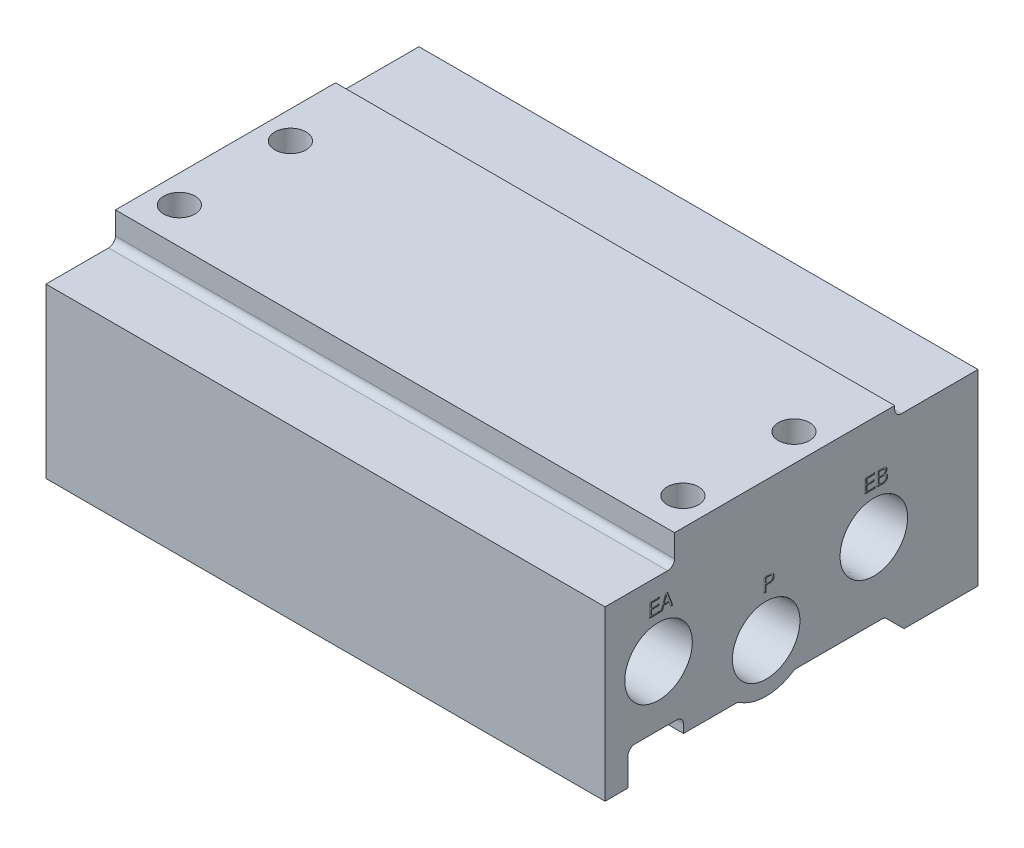
SolidWorks part; units mm, degrees
material "6061-T6 (SS)"
ref_plane "Front" through (0, 0, 0) normal (0, 0, 1) x (1, 0, 0)
ref_plane "Top" through (0, 0, 0) normal (0, 1, 0) x (1, 0, 0)
ref_plane "Right" through (0, 0, 0) normal (1, 0, 0) x (0, 0, -1)
sketch "Alum Ext Sketch" plane through (0, 0, 0) normal (1, 0, 0) x (0, 0, -1)
  line L1 (-26.85, 0) -> (26.85, 0)
  line L2 (-26.85, 0) -> (-26.85, -28.5)
  line L4 (26.85, 0) -> (26.85, -28.5)
  line L7 (0, 5.7104) -> (0, -31.2342) construction
  line L8 (-26.85, -28.5) -> (26.85, -28.5)
  dimension "Depth" = 53.7
  dimension "Height" = 28.5
extrude "Alum Ext" add sketch "Alum Ext Sketch" against normal up to surface (80.5 mm away)
sketch "Bottom_Profile 20 Sketch" [suppressed] plane through (0, 0, 0) normal (1, 0, 0) x (0, 0, -1)
  line L0 (-1, 0) -> (-1, -38.4475) construction
  line L1 (-21.54, -20) -> (-21.54, -13.45)
  line L2 (-24.5, -20) -> (24.5, -20) construction
  line L3 (-21.54, -13.45) -> (-21.1875, -13.45)
  line L4 (-13.8125, -13.45) -> (-4.6875, -13.45)
  line L5 (11.8125, -13.45) -> (2.6875, -13.45)
  line L6 (21.54, -13.45) -> (19.1875, -13.45)
  line L7 (21.54, -20) -> (21.54, -13.45)
  line L8 (24.5, -20) -> (24.5, 0) construction
  line L9 (-24.5, 0) -> (-24.5, -20) construction
  line L10 (24.5, 0) -> (-24.5, 0) construction
  line L11 (21.54, -16.725) -> (24.5, -16.725) construction
  line L12 (-21.54, -16.725) -> (-24.5, -16.725) construction
  line L13 (-24.5, -20) -> (-24.5, 0) construction
  line L14 (-21.54, -20) -> (21.54, -20)
  line L15 (-10.2716, -5) -> (-8.2284, -5)
  line L17 (-10.9481, -11.65) -> (-7.5519, -11.65)
  line L18 (-1, 9.9528) -> (-1, -11.3216) construction
  line L19 (8.9481, -11.65) -> (5.5519, -11.65)
  line L20 (8.2716, -5) -> (6.2284, -5)
  line L21 (24.5, 0) -> (-24.5, 0) construction
  arc A0 (-21.1875, -13.45) -> (-13.8125, -13.45) centre (-17.5, -7.5) ccw
  arc A1 (-4.6875, -13.45) -> (2.6875, -13.45) centre (-1, -7.5) ccw
  arc A2 (19.1875, -13.45) -> (11.8125, -13.45) centre (15.5, -7.5) cw
  arc A3 (-10.7535, -5.6333) -> (-11.3849, -10.9067) centre (-17.5, -7.5) cw
  arc A4 (-10.7535, -5.6333) -> (-10.2716, -5) centre (-10.2716, -5.5) cw
  arc A5 (-10.9481, -11.65) -> (-11.3849, -10.9067) centre (-10.9481, -11.15) cw
  arc A6 (-7.5519, -11.65) -> (-7.1151, -10.9067) centre (-7.5519, -11.15) ccw
  arc A7 (-7.7465, -5.6333) -> (-8.2284, -5) centre (-8.2284, -5.5) ccw
  arc A8 (-7.7465, -5.6333) -> (-7.1151, -10.9067) centre (-1, -7.5) ccw
  arc A9 (5.7465, -5.6333) -> (5.1151, -10.9067) centre (-1, -7.5) cw
  arc A10 (5.7465, -5.6333) -> (6.2284, -5) centre (6.2284, -5.5) cw
  arc A11 (5.5519, -11.65) -> (5.1151, -10.9067) centre (5.5519, -11.15) cw
  arc A12 (8.9481, -11.65) -> (9.3849, -10.9067) centre (8.9481, -11.15) ccw
  arc A13 (8.7535, -5.6333) -> (8.2716, -5) centre (8.2716, -5.5) ccw
  arc A14 (8.7535, -5.6333) -> (9.3849, -10.9067) centre (15.5, -7.5) ccw
  dimension "D1" = 23.5
  dimension "Wall_Radius" = 7
  dimension "D2" = 0.5
  dimension "D4" = 5
  dimension "D3" = 1.8
  dimension "Thickness" = 2.96
  dimension "Port_Loc_Z" = 16.5
  dimension "Port_Loc_Y" = 12.5
  dimension "Body_Thickness" = 13.45
extrude "Bottom_Profile 20" [suppressed] cut sketch "Bottom_Profile 20 Sketch" against normal through all
fillet "Ext_Fillets" [suppressed] radius 0.25
sketch "MGT_Holes Sketch" plane through (0, 0, 0) normal (0, 1, 0) x (1, 0, 0)
  line L1 (-40.25, 26.85) -> (-40.25, -50.1534) construction
  line L2 (-80.5, 26.85) -> (0, 26.85) construction
  line L3 (0, 0) -> (0, 12.4211) construction
  line L4 (-80.5, -26.85) -> (0, -26.85) construction
  line L6 (-80.5, -26.85) -> (-80.5, 26.85) construction
  circle A0 centre (-76.5, 4.35) radius 2.25
  circle A1 centre (-76.5, -11.65) radius 2.25
  circle A4 centre (-4, 4.35) radius 2.25
  circle A5 centre (-4, -11.65) radius 2.25
  dimension "Dia" = 4.5
  dimension "Loc_X" = 4
  dimension "Loc_Z" = 15.2
  dimension "C_2_C" = 16
extrude "MGT_Holes" cut sketch "MGT_Holes Sketch" against normal through all
sketch "Top_Profile_41 Sketch" plane through (0, 0, 0) normal (1, 0, 0) x (0, 0, -1)
  line L0 (-26.85, -4.25) -> (-16.85, -4.25)
  line L1 (-16.85, -4.25) -> (-16.85, 0)
  line L2 (26.85, 0) -> (-26.85, 0) construction
  line L3 (14.85, 0) -> (14.85, -1.5)
  line L4 (14.85, -1.5) -> (26.85, -1.5)
  line L5 (26.85, -28.5) -> (26.85, 0) construction
  line L6 (-26.85, -28.5) -> (26.85, -28.5) construction
  line L7 (-26.85, 0) -> (-26.85, -28.5) construction
  line L8 (26.85, -1.5) -> (26.85, 0)
  line L9 (-26.85, 0) -> (-26.85, -4.25)
  line L10 (26.85, 0) -> (14.85, 0)
  line L11 (-16.85, 0) -> (-26.85, 0)
  dimension "Back" = 12
  dimension "Back Height" = 27
  dimension "Front" = 10
  dimension "Front_Height" = 24.25
extrude "Top_Profile_41" cut sketch "Top_Profile_41 Sketch" against normal through all
sketch "Bottom_Profile_41 Sketch" plane through (0, 0, 0) normal (1, 0, 0) x (0, 0, -1)
  line L0 (16.2, -28.5) -> (13.4, -25.7)
  line L1 (-26.85, -28.5) -> (26.85, -28.5) construction
  line L2 (13.4, -25.7) -> (0.4132, -25.7)
  line L3 (-15.55, -25.7) -> (-15.55, -23.5)
  line L4 (-15.55, -23.5) -> (-23.55, -23.5)
  line L5 (-23.55, -23.5) -> (-23.55, -28.5)
  line L6 (26.85, -28.5) -> (-26.85, -28.5) construction
  line L7 (26.85, -28.5) -> (26.85, -1.5) construction
  line L8 (-26.85, -4.25) -> (-26.85, -28.5) construction
  line L9 (-26.85, -28.5) -> (-26.85, -4.25) construction
  line L10 (-7.7132, -25.7) -> (-15.55, -25.7)
  line L11 (-23.55, -28.5) -> (16.2, -28.5)
  arc A0 (-7.7132, -25.7) -> (0.4132, -25.7) centre (-3.65, -20) ccw
  dimension "D1" = 8.5
  dimension "D2" = 23.2
  dimension "Radius" = 7
  dimension "Back_Width" = 13.45
  dimension "Back_Depth" = 2.8
  dimension "Front_Width" = 3.3
  dimension "Front_Depth" = 5
  dimension "Groove" = 8
  dimension "Angle" = 45
extrude "Bottom_Profile_41" cut sketch "Bottom_Profile_41 Sketch" against normal through all
fillet "Rounds_41" radius 1 7 edges at (-40.25, -4.25, 16.85) (-40.25, -1.5, -14.85) (-40.25, -25.7, -0.4132) (-40.25, -23.5, 23.55) (-40.25, -23.5, 15.55) (-40.25, -25.7, 7.7132) (-40.25, -25.7, -13.4)
sketch "Profile_42 Sketch" [suppressed] plane through (0, 0, 0) normal (1, 0, 0) x (0, 0, -1)
  line L0 (-13.9, -32) -> (-12.9, -31)
  line L1 (-27.85, -32) -> (27.85, -32) construction
  line L2 (-12.9, -31) -> (12.9, -31)
  line L3 (12.9, -31) -> (13.9, -32)
  line L4 (13.9, -32) -> (-13.9, -32)
  line L5 (0, 0) -> (0, -41.5568) construction
  dimension "Width" = 25.8
  dimension "Angle" = 90
  dimension "Depth" = 1
extrude "Profile_42" [suppressed] cut sketch "Profile_42 Sketch" against normal through all
fillet "Fillets_42" [suppressed] radius 0.5
sketch "20 Port Designations Sketch" [suppressed] plane through (2.9671, 0, 3.015) normal (0, 1, 0) x (0, 0, 1)
  line L0 (21.485, -51.4671) -> (-27.515, -51.4671) construction
  line L2 (-27.515, -51.4671) -> (-27.515, -2.9671) construction
  line L3 (21.485, -51.4671) -> (21.485, -2.9671) construction
  text T0 "EA"
  text T1 "P" font "Swis721 BT" height 3.5
  text T2 "EB" font "Swis721 BT" height 3.5
  dimension "D1" = 3
  dimension "D2" = 4
  dimension "D3" = 23
  dimension "D4" = 11
extrude "20 Port Designations" [suppressed] cut sketch "20 Port Designations Sketch" against normal blind 0.1
sketch "20 Port Designations2 Sketch" [suppressed] plane through (-31.3648, 0, 0.1552) normal (0, 1, 0) x (0, 0, -1)
  line L0 (24.6552, -31.3648) -> (-24.3448, -31.3648) construction
  line L1 (24.6552, 17.1352) -> (24.6552, -31.3648) construction
  line L2 (-24.3448, 17.1352) -> (-24.3448, -31.3648) construction
  text T0 "EB"
  text T1 "P"
  text T2 "EA"
  dimension "D1" = 3
  dimension "D2" = 26.5
  dimension "D3" = 4
  dimension "D4" = 11
extrude "20 Port Designations2" [suppressed] cut sketch "20 Port Designations2 Sketch" against normal blind 0.1
hole_wizard "Ports" positions "Ports Loc Sketch" profile "Ports Profile Sketch" size "1/8" standard "ISO"
sketch "Ports Loc Sketch" plane through (0, 0, 0) normal (1, 0, 0) x (0, 0, -1)
  line L1 (-3.65, -20) -> (-3.65, -0.9405) construction
  line L5 (-26.85, -28.5) -> (-23.55, -28.5) construction
  line L7 (-26.85, -4.25) -> (-26.85, -28.5) construction
  point P0 (-3.65, -20)
  point P1 (11.85, -14.9)
  point P3 (-19.15, -14.9)
  dimension "Loc_Z" = 23.2
  dimension "C_2_C-Z" = 15.5
  dimension "C_2_C-Y" = 8.5
  dimension "Loc_Y" = 13.6
sketch "Ports Profile Sketch" plane through (0, -20, 3.65) normal (0, 1, 0) x (0, 0, -1)
  line L0 (0, 0) -> (0, 22.45)
  line L1 (3.95, 18.5) -> (0, 22.45)
  line L2 (-3.95, 18.5) -> (0, 22.45) construction
  line L3 (3.95, 18.5) -> (3.95, 7.4)
  line L4 (3.95, 7.4) -> (4.633, 7.4)
  line L5 (4.633, 7.4) -> (4.864, 0)
  line L6 (-4.633, 7.4) -> (-4.864, 0) construction
  line L7 (4.864, 0) -> (0, 0)
  line L8 (0, -6.35) -> (0, 107.95) construction
  line L11 (-3.95, 7.4) -> (-4.633, 7.4) construction
  dimension "Tap Drill Dia." = 7.9
  dimension "Tap Drill Depth" = 18.5
  dimension "Thread Dia." = 9.728
  dimension "Thread Angle" = 3.576
  dimension "Thread Depth" = 7.4
  dimension "Drill Angle" = 90
hole_wizard "Ports Mirror" positions "Ports Mirror Loc Sketch" profile "Ports Mirror Profile Sketch" size "1/8" standard "ISO"
sketch "Ports Mirror Loc Sketch" plane through (-80.5, 0, 0) normal (-1, 0, 0) x (0, 0, 1)
  point P0 (-11.85, -14.9)
  point P1 (3.65, -20)
  point P4 (19.15, -14.9)
sketch "Ports Mirror Profile Sketch" plane through (-80.5, -14.9, -11.85) normal (0, 1, 0) x (0, 0, 1)
  line L0 (0, 0) -> (0, 15.885)
  line L1 (3.95, 11.935) -> (0, 15.885)
  line L2 (-3.95, 11.935) -> (0, 15.885) construction
  line L3 (3.95, 11.935) -> (3.95, 7.4)
  line L4 (3.95, 7.4) -> (4.633, 7.4)
  line L5 (4.633, 7.4) -> (4.864, 0)
  line L6 (-4.633, 7.4) -> (-4.864, 0) construction
  line L7 (4.864, 0) -> (0, 0)
  line L8 (0, -6.35) -> (0, 107.95) construction
  line L11 (-3.95, 7.4) -> (-4.633, 7.4) construction
  dimension "Tap Drill Dia." = 7.9
  dimension "Tap Drill Depth" = 11.935
  dimension "Thread Dia." = 9.728
  dimension "Thread Angle" = 3.576
  dimension "Thread Depth" = 7.4
  dimension "Drill Angle" = 90
hole_wizard "Pilot Ports" [suppressed] positions "Pilot Ports Loc Sketch" profile "Pilot Ports Profile Sketch" tap size "M5x0.8" standard "JIS"
sketch "Pilot Ports Loc Sketch" [suppressed] plane through (0, 0, 0) normal (1, 0, 0) x (0, 0, -1)
  line L1 (14.1071, -32) -> (27.85, -32) construction
  circle A0 centre (-4.65, -24) radius 4.864 construction
  point P0 (14.75, -4)
  point P1 (-19.35, -4)
  dimension "D2" = 19.4
  dimension "D3" = 14.7
  dimension "D1" = 28
sketch "Pilot Ports Profile Sketch" [suppressed] plane through (0, -4, -14.75) normal (0, 1, 0) x (0, 0, -1)
  line L0 (0, 0) -> (0, 13.6618)
  line L1 (0, 13.6618) -> (2.1, 12.4)
  line L2 (2.1, 12.4) -> (2.1, 10)
  line L3 (2.1, 10) -> (2.5, 10)
  line L4 (2.5, 10) -> (2.5, 0)
  line L5 (2.5, 0) -> (0, 0)
  line L10 (0, 13.6618) -> (-2.1, 12.4) construction
  line L11 (0, -6.35) -> (0, 107.95) construction
  dimension "Tap Drill Dia." = 4.2
  dimension "Tap Drill Depth" = 12.4
  dimension "Thread Major Dia." = 5
  dimension "Thread Depth" = 10
  dimension "Drill Angle" = 118
hole_wizard "Pilot Ports Mirror" [suppressed] positions "Pilot Ports Mirror Loc Sketch" profile "Pilot Ports Mirror Profile Sketch" tap size "M5" standard "ISO"
sketch "Pilot Ports Mirror Loc Sketch" [suppressed] plane through (-101.5, 0, 0) normal (-1, 0, 0) x (0, 0, 1)
  point P0 (19.35, -4)
  point P1 (-14.75, -4)
sketch "Pilot Ports Mirror Profile Sketch" [suppressed] plane through (-101.5, -4, 19.35) normal (0, 1, 0) x (0, 0, 1)
  line L0 (0, 0) -> (0, 13.6618)
  line L1 (0, 13.6618) -> (2.1, 12.4)
  line L2 (2.1, 12.4) -> (2.1, 10)
  line L3 (2.1, 10) -> (2.5, 10)
  line L4 (2.5, 10) -> (2.5, 0)
  line L5 (2.5, 0) -> (0, 0)
  line L10 (0, 13.6618) -> (-2.1, 12.4) construction
  line L11 (0, -6.35) -> (0, 107.95) construction
  dimension "Tap Drill Dia." = 4.2
  dimension "Tap Drill Depth" = 12.4
  dimension "Thread Major Dia." = 5
  dimension "Thread Depth" = 10
  dimension "Drill Angle" = 118
sketch "41,42 Port Labels1 Sketch" plane through (-80.5, 0, 0) normal (-1, 0, 0) x (0, 0, 1)
  text T0 "EB" font "Swis721 BT" height 2
  text T1 "P" font "Swis721 BT" height 2
  text T2 "EA" font "Swis721 BT" height 2
  dimension "D1" = 1.5
  dimension "D2" = 1.5
  dimension "D3" = 6
  dimension "D4" = 6
  dimension "D5" = 6
  dimension "D6" = 0.5
extrude "41,42 Port Labels1" cut sketch "41,42 Port Labels1 Sketch" against normal blind 0.1
sketch "41,42 Port Labels2 Sketch" plane through (0, 0, 0) normal (1, 0, 0) x (0, 0, -1)
  text T0 "EA" font "Swis721 BT" height 2
  text T1 "P" font "Swis721 BT" height 2
  text T2 "EB" font "Swis721 BT" height 2
  dimension "D1" = 6
  dimension "D2" = 6
  dimension "D3" = 0.5
  dimension "D4" = 6
  dimension "D5" = 1.5
  dimension "D6" = 1.5
extrude "41,42 Port Labels2" cut sketch "41,42 Port Labels2 Sketch" against normal blind 0.1
sketch "42 Pilot Labels1 Sketch" [suppressed] plane through (-101.5, 0, 0) normal (-1, 0, 0) x (0, 0, 1)
  text T0 "PE" font "Swis721 BT" height 2
  text T1 "X" font "Swis721 BT" height 2
extrude "42 Pilot Labels1" [suppressed] cut sketch "42 Pilot Labels1 Sketch" against normal blind 0.1
sketch "42 Pilot Labels2 Sketch" [suppressed] plane through (0, 0, 0) normal (1, 0, 0) x (0, 0, -1)
  text T0 "X" font "Swis721 BT" height 2
  text T1 "PE" font "Swis721 BT" height 2
extrude "42 Pilot Labels2" [suppressed] cut sketch "42 Pilot Labels2 Sketch" against normal blind 0.1
sketch "41,42 A,B Labels Sketch" plane through (0, 0, -26.85) normal (0, 0, 1) x (1, 0, 0)
  line L0 (-80.5, -28.5) -> (0, -28.5) construction
  line L1 (-80.5, -1.5) -> (-80.5, -28.5) construction
  line L2 (0, -28.5) -> (0, -1.5) construction
  line L3 (-80.5, -28.5) -> (0, -28.5) construction
  text T0 "A"
  text T1 "B"
  text T2 "A"
  text T3 "B"
  point P12 (-80.5, -15)
  dimension "D1" = 5
  dimension "D2" = 11
  dimension "D3" = 1
  dimension "D4" = 18.5
  dimension "D5" = 8
  dimension "D6" = 4.5
extrude "41,42 A,B Labels" cut sketch "41,42 A,B Labels Sketch" along normal blind 0.1
